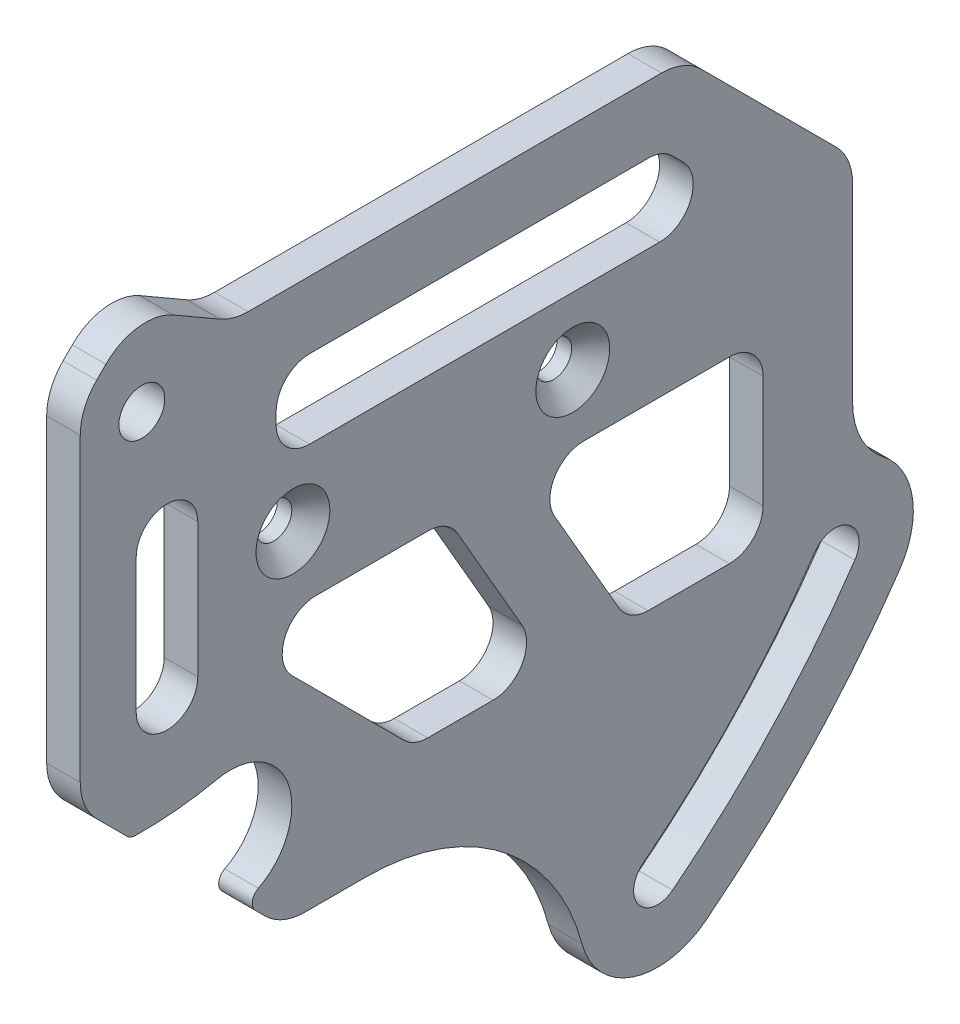
SolidWorks part; units mm, degrees
material "Thornel Mat VMA"
ref_plane "前视基准面" through (0, 0, 0) normal (0, 0, 1) x (1, 0, 0)
ref_plane "上视基准面" through (0, 0, 0) normal (0, 1, 0) x (1, 0, 0)
ref_plane "右视基准面" through (0, 0, 0) normal (1, 0, 0) x (0, 0, -1)
sketch "草图1" plane through (0, 0, 0) normal (1, 0, 0) x (0, 0, -1)
  line L25 (-12.5, 0) -> (12.5, 0) construction
  line L27 (-17.8397, 19) -> (37.5, 19)
  line L28 (-31.5, 19) -> (-31.5, -12)
  line L29 (-31.5, -30) -> (41, -30) construction
  line L30 (37.5, 19) -> (37.5, -19.2873)
  line L31 (-26, 16) -> (36, 16) construction
  line L32 (-26, 16) -> (-26, -26) construction
  line L33 (-26, -26) -> (36, -26) construction
  line L34 (36, 16) -> (36, -26) construction
  line L36 (36, -26) -> (-26, 16) construction
  line L37 (-26, 16) -> (20.0899, -43.0231) construction
  line L39 (-5.9931, -30) -> (-13.5, -30)
  line L40 (-31.5, -12) -> (-13.5, -30)
  line L41 (-31.5, 19) -> (-26.5, 24)
  line L42 (-26.5, 24) -> (-17.8397, 19)
  line L43 (35.9266, -26.1081) -> (-26, 16) construction
  line L44 (-17.701, -6) -> (1.3342, -6)
  line L45 (29.5, -6) -> (29.5, -22)
  line L46 (29.5, -22) -> (17.5, -22)
  line L47 (-1.701, -22) -> (-17.701, -6)
  line L48 (1.3342, -6) -> (10.5718, -22)
  line L49 (8.2624, -6) -> (17.5, -22)
  line L50 (10.5718, -22) -> (-1.701, -22)
  line L51 (8.2624, -6) -> (29.5, -6)
  line L52 (-14, 13) -> (27.5, 13) construction
  line L53 (27.5, 13) -> (27.5, 6) construction
  line L54 (27.5, 6) -> (-14, 6)
  line L55 (-14, 6) -> (-14, 13)
  line L56 (27.5, 6) -> (20.5, 13)
  line L57 (20.5, 13) -> (-14, 13)
  line L58 (-23.75, 5) -> (-23.75, -7) construction
  line L59 (-21, 5) -> (-21, -7)
  line L60 (-26.5, 5) -> (-26.5, -7)
  circle A2 centre (-12.5, 0) radius 1.6
  circle A3 centre (12.5, 0) radius 1.6
  circle A4 centre (-26, 16) radius 2.05
  arc A5 (37.78, -27.2058) -> (34.22, -24.7942) centre (36, -26) ccw construction
  circle A6 centre (-26, 16) radius 72.7366 construction
  circle A7 centre (-26, 16) radius 77.0366 construction
  arc A8 (18.7666, -41.3285) -> (21.4131, -44.7176) centre (20.0899, -43.0231) ccw
  arc A9 (18.7666, -41.3285) -> (34.1487, -24.8992) centre (-26, 16) ccw
  arc A10 (21.4131, -44.7176) -> (37.7045, -27.3171) centre (-26, 16) ccw
  circle A12 centre (-26, 16) radius 74.8866 construction
  arc A13 (13.3276, -44.8319) -> (24.3981, -48.5402) centre (20.0899, -43.0231) ccw
  arc A14 (24.3981, -48.5402) -> (41.7152, -30.0442) centre (-26, 16) ccw
  arc A15 (13.3276, -44.8319) -> (-5.9931, -30) centre (-5.9931, -50) ccw
  arc A17 (37.7045, -27.3171) -> (34.1487, -24.8992) centre (35.9266, -26.1081) ccw
  arc A18 (41.7152, -30.0442) -> (37.5, -19.2873) centre (35.9266, -26.1081) ccw
  arc A19 (-21, 5) -> (-26.5, 5) centre (-23.75, 5) ccw
  arc A20 (-26.5, -7) -> (-21, -7) centre (-23.75, -7) ccw
  point P0 (0, 0)
  point P51 (-23.75, -1)
  dimension "D3" = 3
  dimension "D4" = 30
  dimension "D9" = 16
  dimension "D2" = 3.2
  dimension "D5" = 19
  dimension "D6" = 25
  dimension "D7" = 4.1
  dimension "D8" = 4.3
  dimension "D16" = 7
  dimension "D17" = 40
  dimension "D1" = 25
  dimension "D10" = 62
  dimension "D11" = 26
  dimension "D12" = 42
  dimension "D13" = 45
  dimension "D14" = 18
  dimension "D15" = 17.8
  dimension "D18" = 45
  dimension "D19" = 30
  dimension "D20" = 5
  dimension "D21" = 0.1
  dimension "D22" = 8
  dimension "D23" = 6
  dimension "D24" = 8
  dimension "D25" = 14
  dimension "D26" = 6
  dimension "D27" = 60
  dimension "D28" = 12
  dimension "D29" = 6
  dimension "D30" = 6
  dimension "D31" = 10
  dimension "D32" = 12
  dimension "D33" = 45
  dimension "D34" = 5
  dimension "D35" = 7
  dimension "D36" = 12
  dimension "D37" = 11
extrude "凸台-拉伸1" add sketch "草图1" along normal blind 3
hole_wizard "打孔尺寸(%根据十字)槽沉头木螺钉的类型2" positions "3D草图2" profile "草图3" countersink size "M3" standard "GB" end condition through all
sketch3d "3D草图2"
  line L0 (3, 0, -12.5) -> (0, 0, -12.5) construction
  line L1 (3, 0, 12.5) -> (0, 0, 12.5) construction
  line L2 (3, 0, -12.5) -> (0, 0, -12.5) construction
  point P2 (3, 0, -12.5)
  point P11 (3, 0, 12.5)
  point P15 (3, 0, -12.5)
  point P19 (3, 0, -12.5)
  point P21 (3, 0, -12.5)
sketch "草图3" plane through (3, 0, -12.5) normal (0, 1, 0) x (0, 0, -1)
  line L0 (0, 0) -> (0, 3)
  line L1 (0, 3) -> (1.55, 3)
  line L2 (1.55, 3) -> (1.55, 1.75)
  line L3 (1.55, 1.75) -> (3.3, 0)
  line L5 (3.3, 0) -> (0, 0)
  line L6 (-1.55, 1.75) -> (-3.3, 0) construction
  line L11 (0, -6.35) -> (0, 107.95) construction
  dimension "通孔孔直径" = 3.1
  dimension "通孔孔深度" = 3
  dimension "近端锥形沉头孔直径" = 6.6
  dimension "近端锥形沉头孔角度" = 90
sketch "草图4" plane through (3, 0, 0) normal (1, 0, 0) x (0, 0, -1)
  circle A0 centre (35.9266, -26.1081) radius 11
  arc A1 (37.7045, -27.3171) -> (34.1487, -24.8992) centre (35.9266, -26.1081) ccw construction
  dimension "D1" = 22
fillet "圆角1" radius 7 1 edges at (1.5, -19.2873, -37.5)
sketch "草图5" plane through (3, 0, 0) normal (1, 0, 0) x (0, 0, -1)
  line L0 (-26, 16) -> (-18.0994, -21.1696) construction
  line L1 (-31.5, -12) -> (-13.5, -30) construction
  line L2 (-26, 16) -> (-26, -3.3206) construction
  line L3 (-27.0159, -16.4841) -> (-16.9515, -26.5485)
  circle A0 centre (-26, 16) radius 38 construction
  arc A1 (-16.9515, -26.5485) -> (-19.2429, -15.7898) centre (-18.0994, -21.1696) ccw
  arc A2 (-19.2429, -15.7898) -> (-27.0159, -16.4841) centre (-26, 16) cw
  dimension "D1" = 76
  dimension "D2" = 11
  dimension "D3" = 12
extrude "切除-拉伸1" cut sketch "草图5" against normal blind 10
fillet "圆角2" radius 1 2 edges at (1.5, -16.4841, 27.0159) (1.5, -26.5485, 16.9515)
chamfer "倒角1" distance 15 angle 45 1 edges at (1.5, 19, -37.5)
fillet "圆角3" radius 5 7 edges at (1.5, -12, 31.5) (1.5, -30, 13.5) (1.5, 4, -37.5) (1.5, 19, -22.5) (1.5, 19, 17.8397) (1.5, 24, 26.5) (1.5, 19, 31.5)
fillet "圆角4" radius 3 12 edges at (1.5, 6, 14) (1.5, 6, -27.5) (1.5, 13, -20.5) (1.5, 13, 14) (1.5, -6, -29.5) (1.5, -22, -17.5) (1.5, -22, -29.5) (1.5, -6, -8.2624) (1.5, -22, -10.5718) (1.5, -6, -1.3342) (1.5, -22, 1.701) (1.5, -6, 17.701)
